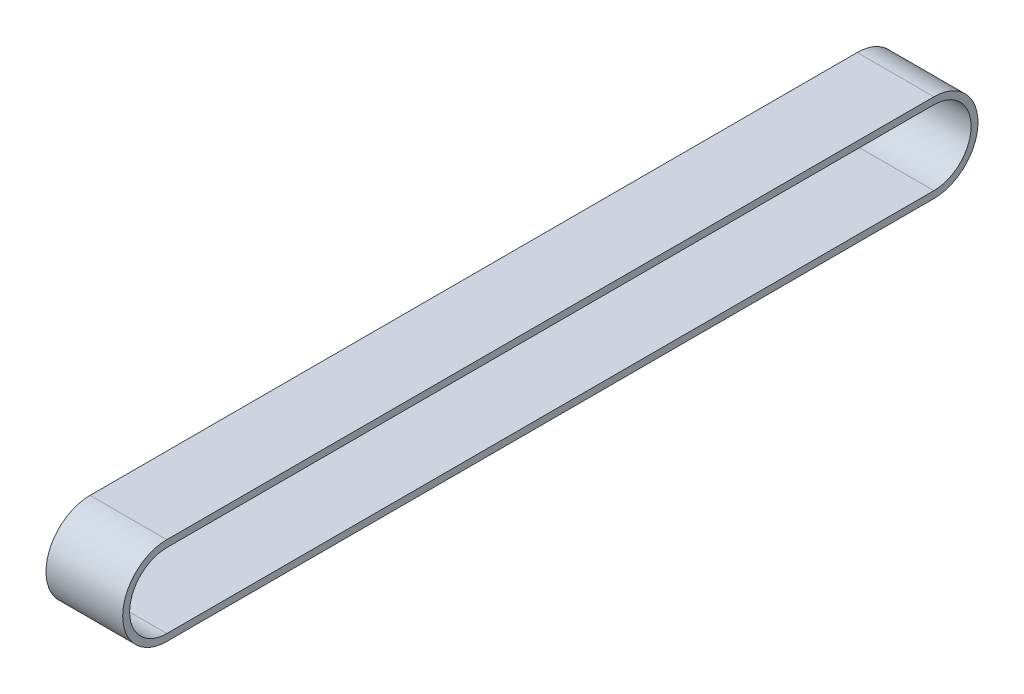
SolidWorks part; units mm, degrees
material "PUR"
ref_plane "Front" through (0, 0, 0) normal (0, 0, 1) x (1, 0, 0)
ref_plane "Top" through (0, 0, 0) normal (0, 1, 0) x (1, 0, 0)
ref_plane "Right" through (0, 0, 0) normal (1, 0, 0) x (0, 0, -1)
sketch "Sketch1" plane through (0, 0, 0) normal (1, 0, 0) x (0, 0, -1)
  line L0 (-127, 0) -> (127, 0) construction
  line L1 (-127, 14.605) -> (127, 14.605)
  line L2 (-127, -14.605) -> (127, -14.605)
  line L3 (-127, 0) -> (127, 0) construction
  line L4 (-127, 12.319) -> (127, 12.319)
  line L5 (-127, -12.319) -> (127, -12.319)
  arc A0 (-127, 14.605) -> (-127, -14.605) centre (-127, 0) ccw
  arc A1 (127, -14.605) -> (127, 14.605) centre (127, 0) ccw
  arc A2 (-127, 12.319) -> (-127, -12.319) centre (-127, 0) ccw
  arc A3 (127, -12.319) -> (127, 12.319) centre (127, 0) ccw
  point P2 (0, 0)
  point P9 (0, 0)
  dimension "D2" = 24.638
  dimension "D1" = 2.286
  dimension "D3" = 254
extrude "Boss-Extrude1" add sketch "Sketch1" along normal mid plane 25.4
